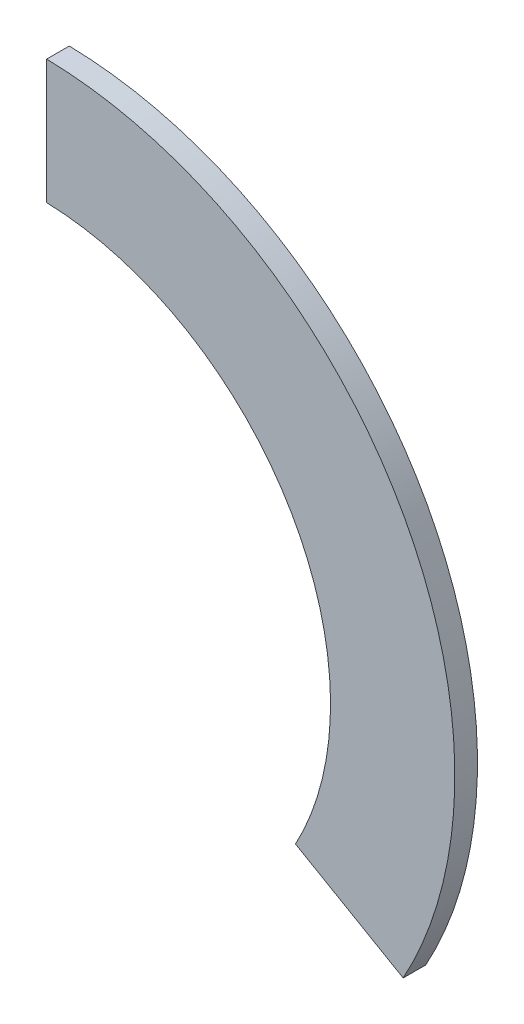
SolidWorks part; units mm, degrees
material "Teck"
ref_plane "Plan de face" through (0, 0, 0) normal (0, 0, 1) x (1, 0, 0)
ref_plane "Plan de dessus" through (0, 0, 0) normal (0, 1, 0) x (1, 0, 0)
ref_plane "Plan de droite" through (0, 0, 0) normal (1, 0, 0) x (0, 0, -1)
sketch "Esquisse1" plane through (0, 0, 0) normal (0, 0, 1) x (1, 0, 0)
  line L0 (1.5, 73.5947) -> (1.5, 51.6282)
  line L1 (64.4849, -35.4984) -> (45.4613, -24.5151)
  line L2 (0, 73.61) -> (0, 0) construction
  line L3 (0, 0) -> (63.7481, -36.805) construction
  arc A0 (1.5, 51.6282) -> (45.4613, -24.5151) centre (0, 0) cw
  circle A1 centre (0, 0) radius 51.65 construction
  arc A2 (1.5, 73.5947) -> (64.4849, -35.4984) centre (0, 0) cw
  circle A3 centre (0, 0) radius 73.61 construction
  dimension "D1" = 120
  dimension "D2" = 1.5
  dimension "D3" = 1.5
extrude "Boss.-Extru.1" add sketch "Esquisse1" along normal blind 4 contours L0 A0 L1 A2
